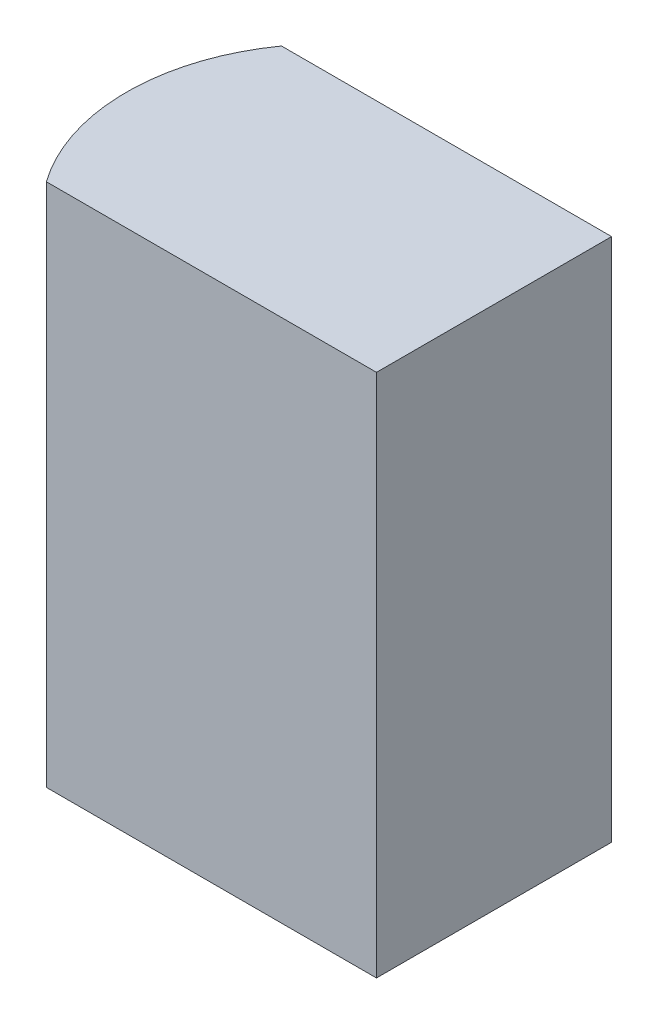
SolidWorks part; units mm, degrees
ref_plane "Front Plane" through (0, 0, 0) normal (0, 0, 1) x (1, 0, 0)
ref_plane "Top Plane" through (0, 0, 0) normal (0, 1, 0) x (1, 0, 0)
ref_plane "Right Plane" through (0, 0, 0) normal (1, 0, 0) x (0, 0, -1)
sketch "Sketch1" plane through (0, 0, 0) normal (0, 1, 0) x (1, 0, 0)
  line L0 (-182.5, -130) -> (182.5, -130)
  line L1 (-182.5, 130) -> (182.5, 130)
  line L2 (182.5, -130) -> (182.5, 130)
  line L3 (-182.5, -130) -> (182.5, 130) construction
  line L4 (-182.5, 130) -> (182.5, -130) construction
  arc A0 (-182.5, 130) -> (-182.5, -130) centre (0, 0) ccw
  point P0 (0, 0)
  point P6 (0, 0)
  dimension "D1" = 260
  dimension "D2" = 182.5
extrude "Boss-Extrude1" add sketch "Sketch1" along normal blind 580
